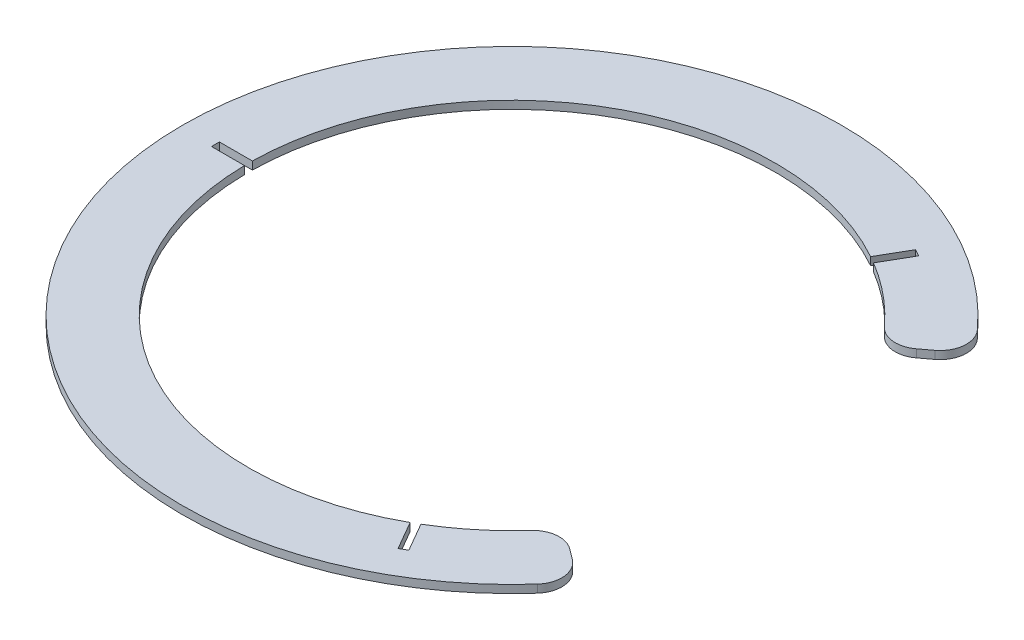
SolidWorks part; units mm, degrees
ref_plane "Front Plane" through (0, 0, 0) normal (0, 0, 1) x (1, 0, 0)
ref_plane "Top Plane" through (0, 0, 0) normal (0, 1, 0) x (1, 0, 0)
ref_plane "Right Plane" through (0, 0, 0) normal (1, 0, 0) x (0, 0, -1)
sketch "Sketch1" plane through (0, 0, 0) normal (0, 1, 0) x (1, 0, 0)
  circle A0 centre (0, 0) radius 125
  dimension "D1" = 250
extrude "Boss-Extrude1" add sketch "Sketch1" along normal blind 3
sketch "Sketch2" plane through (0, 3, 0) normal (0, 1, 0) x (1, 0, 0)
  circle A0 centre (0, 0) radius 100
  dimension "D1" = 200
extrude "Cut-Extrude1" cut sketch "Sketch2" against normal blind 3
sketch "Sketch3" plane through (0, 3, 0) normal (0, 1, 0) x (1, 0, 0)
  line L0 (182.6141, 0) -> (-182.6141, 0) construction
  line L2 (0, -164.1797) -> (0, 164.1797) construction
  line L3 (-87.5, -1.5) -> (-112.5, -1.5)
  line L4 (-87.5, -1.5) -> (-87.5, 1.5)
  line L5 (-87.5, 1.5) -> (-112.5, 1.5)
  line L6 (-112.5, -1.5) -> (-112.5, 1.5)
  line L7 (-87.5, -1.5) -> (-112.5, 1.5) construction
  line L8 (-87.5, 1.5) -> (-112.5, -1.5) construction
  circle A0 centre (0, 0) radius 100 construction
  point P0 (-100, 0)
  point P4 (0, 0)
  point P7 (0, 0)
  dimension "D1" = 25
  dimension "D2" = 3
extrude "Cut-Extrude2" cut sketch "Sketch3" against normal blind 3
pattern_circular "CirPattern1" count 3 over 360 about axis through (0, 0, 0) along (0, 1, 0) of "Cut-Extrude2"
sketch "Sketch4" plane through (0, 3, 0) normal (0, 1, 0) x (1, 0, 0)
  line L0 (80, 60) -> (80, -60) construction
  line L1 (80, -60) -> (99.9826, -75.0233)
  line L2 (80, 60) -> (100, 75)
  arc A0 (80, 60) -> (80, -60) centre (0, 0) cw
  arc A1 (51.2934, -85.8428) -> (51.2934, 85.8428) centre (0, 0) ccw construction
  circle A2 centre (0, 0) radius 125 construction
  arc A3 (100, 75) -> (99.9826, -75.0233) centre (0, 0) cw
  dimension "D1" = 120
extrude "Cut-Extrude3" cut sketch "Sketch4" against normal blind 3
fillet "Fillet1" radius 10 4 edges at (80, 1.5, 60) (99.9826, 1.5, 75.0233) (100, 1.5, -75) (80, 1.5, -60)
